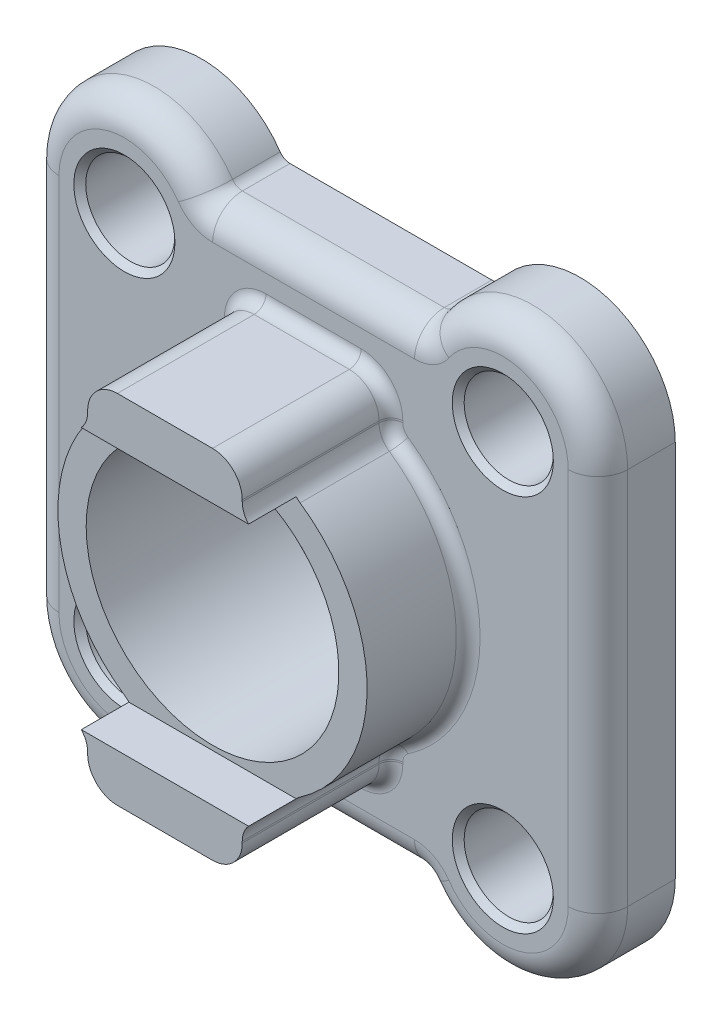
SolidWorks part; units mm, degrees
material "Латунь"
ref_plane "Спереди" through (0, 0, 0) normal (0, 0, 1) x (1, 0, 0)
ref_plane "Сверху" through (0, 0, 0) normal (0, 1, 0) x (1, 0, 0)
ref_plane "Справа" through (0, 0, 0) normal (1, 0, 0) x (0, 0, -1)
sketch "Эскиз1" plane through (0, 0, 0) normal (0, 0, 1) x (1, 0, 0)
  line L0 (-57.3623, 0) -> (78.2728, 0) construction
  line L1 (0, 69.7956) -> (0, -77.425) construction
  line L2 (0, 0) -> (-35.1159, -35.1159) construction
  line L3 (-18.069, 40) -> (18.069, 40)
  line L4 (-47.8198, 31.8198) -> (-47.8198, -31.8198)
  line L5 (47.8198, 31.8198) -> (47.8198, -31.8198)
  line L7 (-18.069, -40) -> (18.069, -40)
  circle A0 centre (0, 0) radius 45 construction
  arc A1 (-47.8198, -31.8198) -> (-18.069, -40) centre (-31.8198, -31.8198) ccw
  arc A2 (47.8198, -31.8198) -> (18.069, -40) centre (31.8198, -31.8198) cw
  arc A3 (-47.8198, 31.8198) -> (-18.069, 40) centre (-31.8198, 31.8198) cw
  arc A4 (47.8198, 31.8198) -> (18.069, 40) centre (31.8198, 31.8198) ccw
  circle A9 centre (0, 0) radius 21.25
  circle A10 centre (-31.8198, 31.8198) radius 7.5
  circle A11 centre (31.8198, 31.8198) radius 7.5
  circle A12 centre (31.8198, -31.8198) radius 7.5
  circle A13 centre (-31.8198, -31.8198) radius 7.5
  point P5 (0, 0)
  point P12 (-31.8198, -31.8198)
  dimension "D3" = 90
  dimension "D5" = 16
  dimension "D7" = 42.5
  dimension "D8" = 15
  dimension "D9" = 15
  dimension "D10" = 15
  dimension "D11" = 15
  dimension "D2" = 80
  dimension "D4" = 45
extrude "Бобышка-Вытянуть1" add sketch "Эскиз1" along normal blind 13
sketch "Эскиз2" plane through (0, 0, 13) normal (0, 0, 1) x (1, 0, 0)
  line L0 (-59.9291, 0) -> (72.6799, 0) construction
  line L1 (0, 44.8585) -> (0, -48.4358) construction
  line L2 (8, -30) -> (-8, -30)
  line L3 (13, -25) -> (13, -24.7184)
  line L4 (8, 30) -> (-8, 30)
  line L5 (-13, -25) -> (-13, -24.7184)
  line L6 (-13, 24.7184) -> (-13, 25)
  line L7 (13, 24.7184) -> (13, 25)
  circle A0 centre (0, 0) radius 21.25 construction
  circle A1 centre (0, 0) radius 21.25
  arc A2 (-14.7333, 21.4226) -> (-14.7333, -21.4226) centre (0, 0) ccw
  arc A3 (8, -30) -> (13, -25) centre (8, -25) ccw
  arc A4 (-8, -30) -> (-13, -25) centre (-8, -25) cw
  arc A5 (-8, 30) -> (-13, 25) centre (-8, 25) ccw
  arc A6 (13, 25) -> (8, 30) centre (8, 25) ccw
  arc A7 (14.7333, -21.4226) -> (14.7333, 21.4226) centre (0, 0) ccw
  arc A8 (13, 24.7184) -> (14.7333, 21.4226) centre (17, 24.7184) ccw
  arc A9 (-14.7333, 21.4226) -> (-13, 24.7184) centre (-17, 24.7184) ccw
  arc A11 (-14.7333, -21.4226) -> (-13, -24.7184) centre (-17, -24.7184) cw
  arc A12 (14.7333, -21.4226) -> (13, -24.7184) centre (17, -24.7184) ccw
  point P27 (13, 22.5167)
  point P30 (-13, 22.5167)
  dimension "D1" = 60
  dimension "D4" = 5
  dimension "D5" = 4
  dimension "D2" = 52
  dimension "D3" = 26
extrude "Бобышка-Вытянуть4" add sketch "Эскиз2" along normal blind 25
sketch "Эскиз3" plane through (0, 0, 38) normal (0, 0, 1) x (1, 0, 0)
  line L0 (-46.9794, 0) -> (51.5298, 0) construction
  line L1 (-14.0657, 22) -> (14.0657, 22)
  line L2 (-14.0657, -22) -> (14.0657, -22)
  arc A2 (-14.7333, 21.4226) -> (-14.7333, -21.4226) centre (0, 0) ccw construction
  arc A3 (14.7333, -21.4226) -> (14.7333, 21.4226) centre (0, 0) ccw construction
  arc A4 (13, 24.7184) -> (14.7333, 21.4226) centre (17, 24.7184) ccw construction
  arc A5 (-14.7333, 21.4226) -> (-13, 24.7184) centre (-17, 24.7184) ccw construction
  arc A6 (14.7333, -21.4226) -> (13, -24.7184) centre (17, -24.7184) ccw construction
  arc A7 (-13, -24.7184) -> (-14.7333, -21.4226) centre (-17, -24.7184) ccw construction
  arc A12 (-14.7333, 21.4226) -> (-14.7333, -21.4226) centre (0, 0) ccw
  arc A13 (14.7333, -21.4226) -> (14.7333, 21.4226) centre (0, 0) ccw
  arc A14 (14.0657, 22) -> (14.7333, 21.4226) centre (17, 24.7184) ccw
  arc A15 (-14.7333, 21.4226) -> (-14.0657, 22) centre (-17, 24.7184) ccw
  arc A16 (14.7333, -21.4226) -> (14.0657, -22) centre (17, -24.7184) ccw
  arc A17 (-14.0657, -22) -> (-14.7333, -21.4226) centre (-17, -24.7184) ccw
  dimension "D1" = 44
extrude "Вырез-Вытянуть4" cut sketch "Эскиз3" against normal offset from surface (8 mm away) 30 up to face at (-24.3198, -31.8198, 0)
fillet "Скругление5" radius 2 20 edges at (-11.5355, -28.5355, 13) (-13, -24.8592, 13) (-13.4598, -22.8565, 13) (-26, 0, 13) (-13.4598, 22.8565, 13) (-13, 24.8592, 13) (-11.5355, 28.5355, 13) (0, 30, 13) (11.5355, 28.5355, 13) (13, 24.8592, 13) (13.4598, 22.8565, 13) (26, 0, 13) (13.4598, -22.8565, 13) (13, -24.8592, 13) (11.5355, -28.5355, 13) (-18.069, 40, 6.5) (18.069, 40, 6.5) (0, -30, 13) (18.069, -40, 6.5) (-18.069, -40, 6.5)
fillet "Скругление6" radius 5 12 edges at (36.5567, 47.1025, 13) (17.9073, 40.2305, 13) (0, 40, 13) (-17.9073, 40.2305, 13) (-36.5567, 47.1025, 13) (-47.8198, 0, 13) (-36.5567, -47.1025, 13) (-17.9073, -40.2305, 13) (0, -40, 13) (17.9073, -40.2305, 13) (36.5567, -47.1025, 13) (47.8198, 0, 13)
chamfer "Фаска1" distance 1 angle 45 8 edges at (-24.3198, -31.8198, 0) (-24.3198, -31.8198, 13) (-24.3198, 31.8198, 0) (-24.3198, 31.8198, 13) (39.3198, 31.8198, 0) (39.3198, 31.8198, 13) (39.3198, -31.8198, 0) (39.3198, -31.8198, 13)
